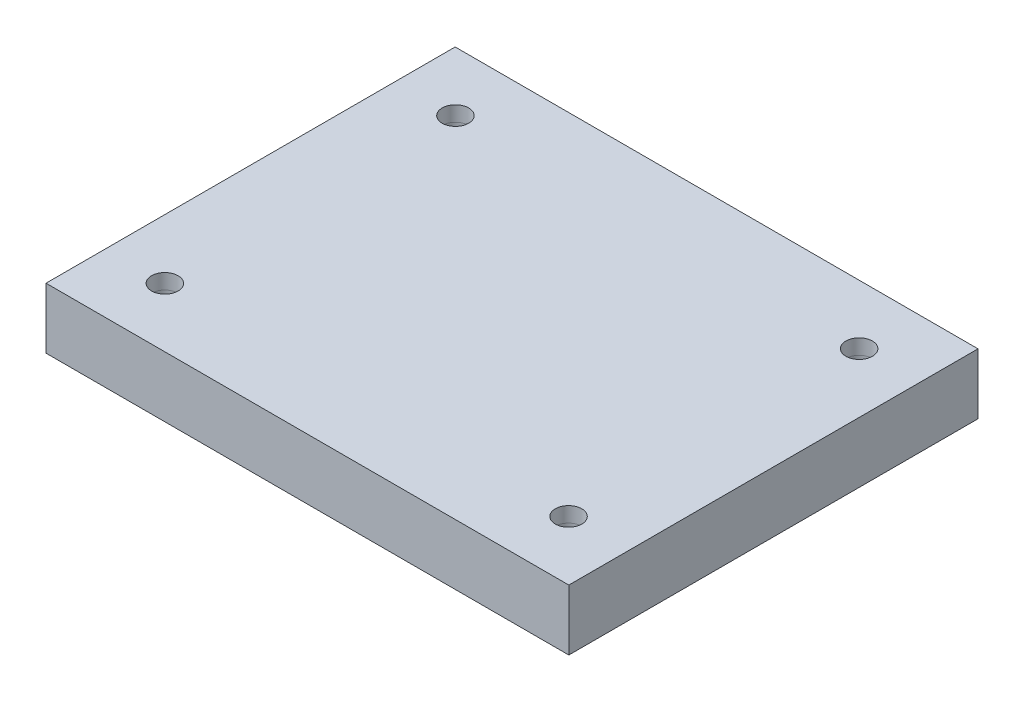
SolidWorks part; units mm, degrees
ref_plane "Front Plane" through (0, 0, 0) normal (0, 0, 1) x (1, 0, 0)
ref_plane "Top Plane" through (0, 0, 0) normal (0, 1, 0) x (1, 0, 0)
ref_plane "Right Plane" through (0, 0, 0) normal (1, 0, 0) x (0, 0, -1)
sketch "Sketch1" plane through (0, 0, 0) normal (0, 1, 0) x (1, 0, 0)
  line L0 (-34.5, -27) -> (-34.5, 27)
  line L1 (-30.5, -23) -> (30.5, -23)
  line L2 (-30.5, -23) -> (-30.5, 23)
  line L3 (-30.5, 23) -> (30.5, 23)
  line L4 (30.5, -23) -> (30.5, 23)
  line L5 (-30.5, -23) -> (30.5, 23) construction
  line L6 (-30.5, 23) -> (30.5, -23) construction
  line L7 (-34.5, 27) -> (34.5, 27)
  line L8 (34.5, -27) -> (34.5, 27)
  line L9 (-34.5, -27) -> (34.5, -27)
  point P0 (0, 0)
  dimension "D1" = 46
  dimension "D2" = 61
  dimension "D3" = 4
extrude "Boss-Extrude1" add sketch "Sketch1" along normal blind 6
sketch "Sketch2" plane through (0, 6, 0) normal (0, 1, 0) x (1, 0, 0)
  line L0 (0, -3.3) -> (0, 3.3) construction
  line L1 (-34.5, -27) -> (34.5, -27)
  line L2 (-34.5, -27) -> (-34.5, 27)
  line L3 (-34.5, 27) -> (34.5, 27)
  line L4 (34.5, -27) -> (34.5, 27)
  line L5 (-3.3, 0) -> (3.3, 0) construction
  circle A0 centre (-26.6383, 19.175) radius 1.75
  circle A1 centre (26.6383, 19.175) radius 1.75
  circle A2 centre (26.6383, -19.175) radius 1.75
  circle A3 centre (-26.6383, -19.175) radius 1.75
  dimension "D1" = 53.2767
  dimension "D3" = 3.5
  dimension "D2" = 38.35
extrude "Boss-Extrude2" add sketch "Sketch2" along normal blind 2
sketch "Sketch3" plane through (0, 6, 0) normal (0, -1, 0) x (1, 0, 0)
  circle A0 centre (-26.6383, 19.175) radius 3.9
  circle A1 centre (-26.6383, -19.175) radius 3.9
  circle A2 centre (26.6383, -19.175) radius 3.9
  circle A3 centre (26.6383, 19.175) radius 3.9
  circle A4 centre (-26.6383, 19.175) radius 1.75 construction
  circle A5 centre (26.6383, -19.175) radius 1.75 construction
  circle A6 centre (26.6383, 19.175) radius 1.75 construction
  circle A7 centre (-26.6383, -19.175) radius 1.75 construction
  circle A8 centre (26.6383, -19.175) radius 1.75
  circle A9 centre (26.6383, 19.175) radius 1.75
  circle A10 centre (-26.6383, 19.175) radius 1.75
  circle A11 centre (-26.6383, -19.175) radius 1.75
  dimension "D1" = 7.8
extrude "Boss-Extrude5" add sketch "Sketch3" along normal blind 6 separate body
